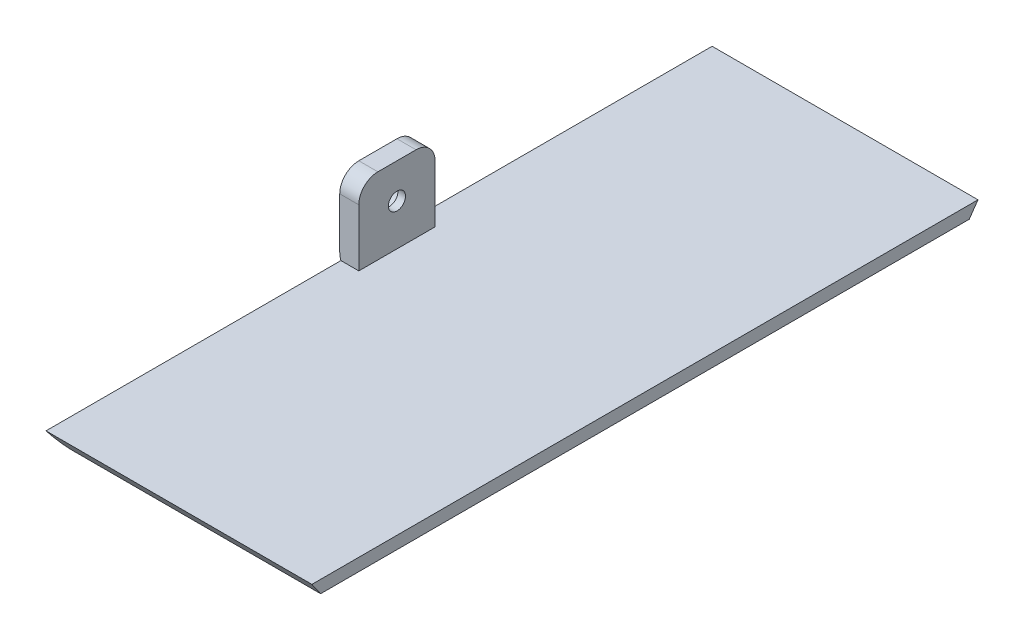
SolidWorks part; units mm, degrees
ref_plane "Front Plane" through (0, 0, 0) normal (1, 0, 0) x (0, 1, 0)
ref_plane "Top Plane" through (0, 0, 0) normal (0, 0, 1) x (0, 1, 0)
ref_plane "Right Plane" through (0, 0, 0) normal (0, 1, 0) x (-1, 0, 0)
sketch "Sketch1" plane through (0, 0, 0) normal (1, 0, 0) x (0, 1, 0)
  line L0 (-1.6383, 85) -> (1.6383, 87.2943)
  line L4 (1.6383, -87.2943) -> (1.6383, 87.2943)
  line L5 (-1.6383, -85) -> (-1.6383, 85)
  line L6 (1.6383, 0) -> (-1.6383, 0) construction
  line L7 (-1.6383, -85) -> (1.6383, -87.2943)
  point P2 (0, 0)
  point P3 (1.6383, 0)
  point P5 (-1.6383, 0)
  dimension "D1" = 55
  dimension "D2" = 4
  dimension "D3" = 85
extrude "Boss-Extrude1" add sketch "Sketch1" along normal blind 70
sketch "Sketch4" plane through (0, 1.6383, 0) normal (0, 1, 0) x (-1, 0, 0)
  line L0 (0, -87.2943) -> (0, 87.2943) construction
  line L1 (-5, 10) -> (0, 10)
  line L2 (-5, 10) -> (-5, -10)
  line L3 (-5, -10) -> (0, -10)
  line L4 (0, 10) -> (0, -10)
  line L5 (-5, -10) -> (-0.3064, -10) construction
  point P6 (0, -9.9427)
  point P9 (-5, -10)
extrude "Boss-Extrude2" add sketch "Sketch4" along normal blind 20
sketch "Sketch5" plane through (0, 0, 0) normal (0, 0, 1) x (0, 1, 0)
  line L0 (-1.6383, -5) -> (-1.6383, 0)
  line L1 (-1.6383, 0) -> (3.3617, 0)
  arc A0 (3.3617, 0) -> (-1.6383, -5) centre (3.3617, -5) ccw
  arc A1 (3.3617, 0) -> (-1.6383, -5) centre (3.3617, -5) ccw construction
  point P8 (3.3617, 0.6637)
  point P10 (3.6231, 0)
  dimension "D1" = 10
extrude "Cut-Extrude2" cut sketch "Sketch5" against normal through all and the other way through all contours A0 L1 L0
sketch "Sketch6" plane through (0, 0, 0) normal (-1, 0, 0) x (0, -1, 0)
  line L1 (-21.6383, -10) -> (-3.3617, -10)
  line L2 (-21.6383, -10) -> (-21.6383, 10)
  line L3 (-21.6383, 10) -> (-3.3617, 10)
  line L4 (-3.3617, -10) -> (-3.3617, 10)
  line L5 (-21.6383, -10) -> (-3.3617, 10) construction
  line L6 (-21.6383, 10) -> (-3.3617, -10) construction
  circle A0 centre (-12.5, 0) radius 2.25
  point P0 (-12.5, 0)
  dimension "D1" = 4.5
extrude "Cut-Extrude3" cut sketch "Sketch6" against normal up to next contours A0
sketch "Sketch7" plane through (0, 0, 0) normal (-1, 0, 0) x (0, -1, 0)
  circle A2 centre (-12.5, 0) radius 3.75
  circle A3 centre (-12.5, 0) radius 3.75
  dimension "D1" = 1.5
extrude "Cut-Extrude4" cut sketch "Sketch7" against normal blind 3
fillet "Fillet1" radius 5 2 edges at (2.5, 21.6383, 10) (2.5, 21.6383, -10)
